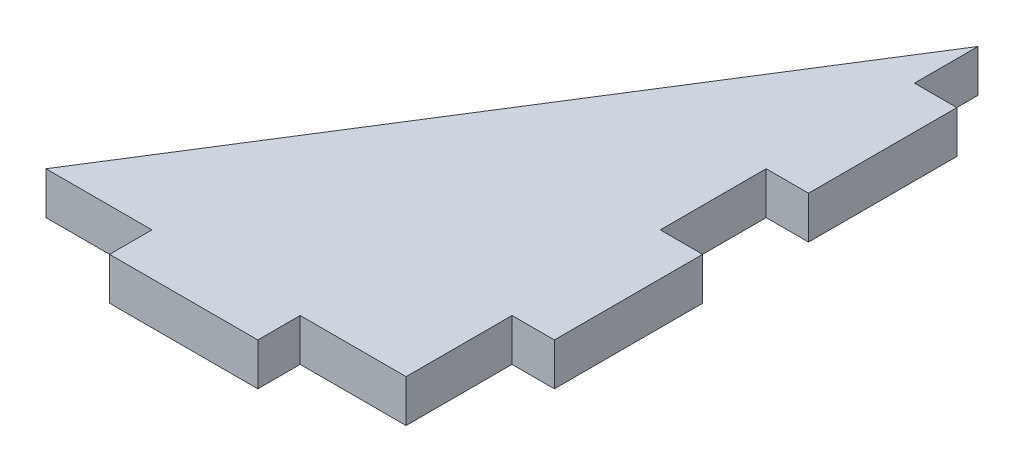
SolidWorks part; units mm, degrees
ref_plane "Front Plane" through (0, 0, 0) normal (0, 0, 1) x (1, 0, 0)
ref_plane "Top Plane" through (0, 0, 0) normal (0, 1, 0) x (1, 0, 0)
ref_plane "Right Plane" through (0, 0, 0) normal (1, 0, 0) x (0, 0, -1)
sketch "Sketch1" plane through (0, 0, 0) normal (0, 1, 0) x (1, 0, 0)
  line L0 (0, 0) -> (-17, 0)
  line L1 (-17, 0) -> (0, 27)
  line L2 (0, 27) -> (0, 0)
  line L4 (-12, 0) -> (-5, 0)
  line L5 (-12, 0) -> (-12, -2)
  line L6 (-12, -2) -> (-5, -2)
  line L7 (-5, 0) -> (-5, -2)
  line L8 (0, 5) -> (2, 5)
  line L9 (0, 5) -> (0, 12)
  line L10 (0, 12) -> (2, 12)
  line L11 (2, 5) -> (2, 12)
  line L12 (0, 17) -> (2, 17)
  line L13 (0, 17) -> (0, 24)
  line L14 (0, 24) -> (2, 24)
  line L15 (2, 17) -> (2, 24)
  dimension "D1" = 2
  dimension "D2" = 2
  dimension "D3" = 2
  dimension "D4" = 7
  dimension "D5" = 7
  dimension "D6" = 7
  dimension "D7" = 17
  dimension "D8" = 27
  dimension "D9" = 5
  dimension "D10" = 5
  dimension "D11" = 5
  dimension "D12" = 5
  dimension "D13" = 3
extrude "Boss-Extrude1" add sketch "Sketch1" along normal blind 2 contours L2 L1 L0 | L7 L0 L5 L6 | L8 L11 L10 L2 | L12 L15 L14 L2
